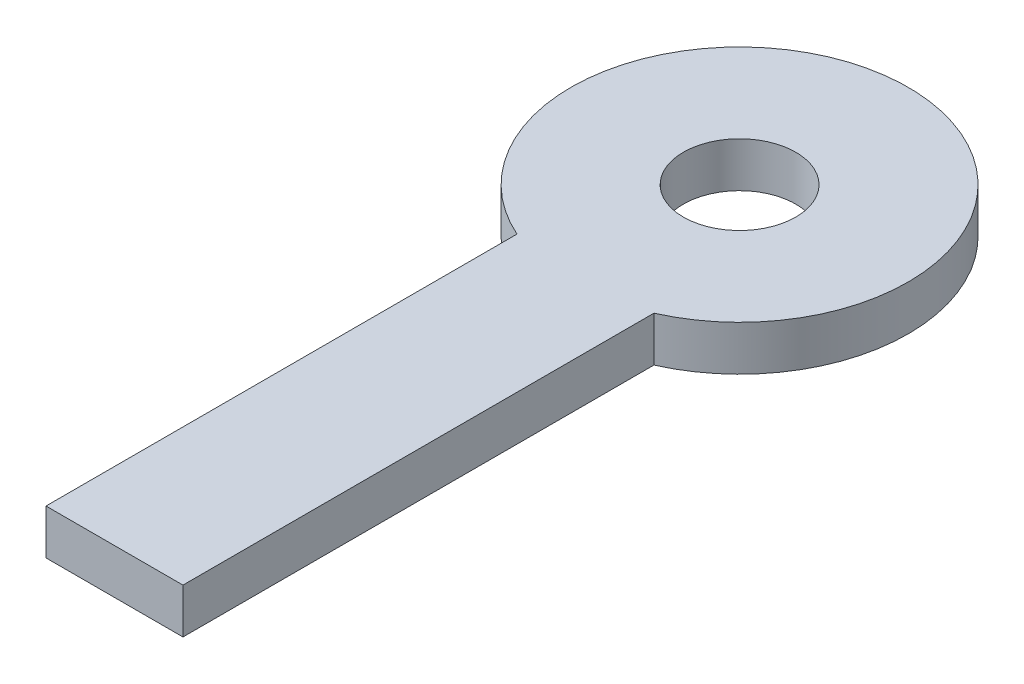
SolidWorks part; units mm, degrees
ref_plane "Front Plane" through (0, 0, 0) normal (0, 0, 1) x (1, 0, 0)
ref_plane "Top Plane" through (0, 0, 0) normal (0, 1, 0) x (1, 0, 0)
ref_plane "Right Plane" through (0, 0, 0) normal (1, 0, 0) x (0, 0, -1)
sketch "Sketch2" plane through (0, 0, 0) normal (0, 1, 0) x (1, 0, 0)
  line L0 (-15.4711, -34.8174) -> (-15.4711, -141.2185)
  line L1 (15.4711, -34.8174) -> (15.4711, -141.2185)
  line L2 (-15.4711, -141.2185) -> (15.4711, -141.2185)
  arc A0 (15.4711, -34.8174) -> (-15.4711, -34.8174) centre (0, 0) ccw
  circle A1 centre (0, 0) radius 12.7
  dimension "D1" = 25.4
  dimension "D2" = 76.2
extrude "Boss-Extrude2" add sketch "Sketch2" along normal blind 10.16
